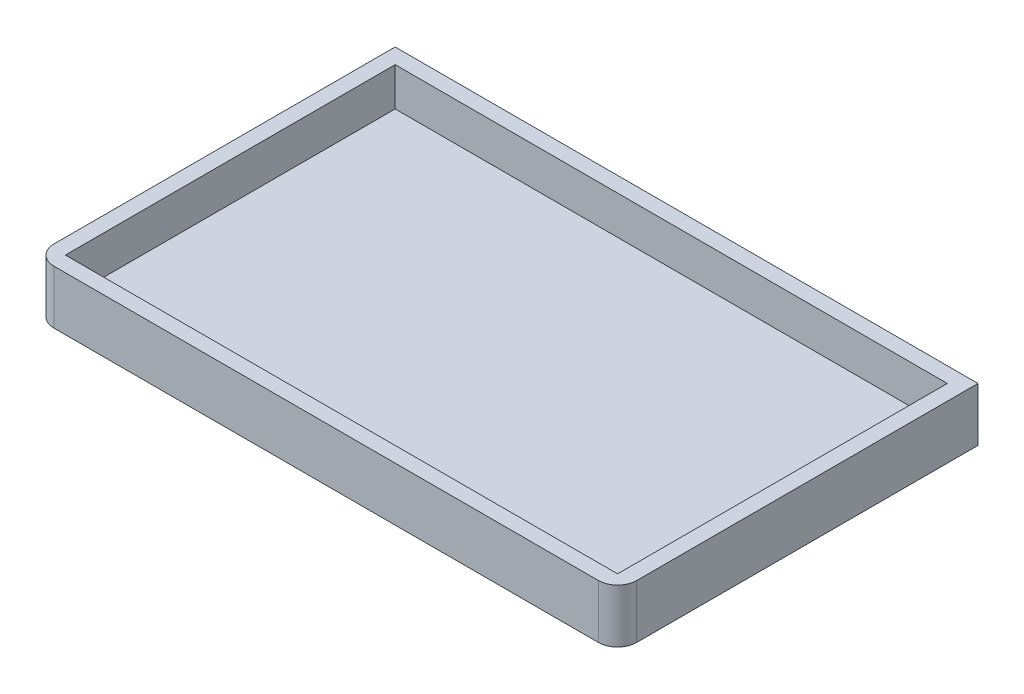
SolidWorks part; units mm, degrees
ref_plane "Front Plane" through (0, 0, 0) normal (0, 0, 1) x (1, 0, 0)
ref_plane "Top Plane" through (0, 0, 0) normal (0, 1, 0) x (1, 0, 0)
ref_plane "Right Plane" through (0, 0, 0) normal (1, 0, 0) x (0, 0, -1)
sketch "Sketch2" plane through (0, 0, 0) normal (0, 0, 1) x (1, 0, 0)
  line L1 (0, 0) -> (50, 0)
  line L2 (0, 0) -> (0, 41)
  line L3 (0, 41) -> (50, 41)
  line L4 (50, 0) -> (50, 41)
  dimension "D1" = 50
  dimension "D2" = 41
extrude "Boss-Extrude1" add sketch "Sketch2" along normal blind 4
sketch "Sketch4" plane through (0, 41, 0) normal (0, 1, 0) x (1, 0, 0)
  line L1 (-51, 0) -> (-51, -94)
  line L2 (101, 0) -> (101, -94)
  line L3 (-51, -94) -> (101, -94)
  line L4 (101, 0) -> (-51, 0) construction
  line L5 (25, 0) -> (25, -94) construction
  line L6 (-51, 0) -> (101, 0)
  line L7 (50, 0) -> (0, 0) construction
  point P1 (0, 0)
  point P4 (0, 0)
  dimension "D1" = 152
  dimension "D2" = 94
extrude "Boss-Extrude2" add sketch "Sketch4" along normal blind 14
sketch3d "3DSketch1"
  line L0 (97, 55, 90) -> (97, 55, 4)
  line L1 (97, 55, 4) -> (-47, 55, 4)
  line L2 (-47, 55, 4) -> (-47, 55, 90)
  line L3 (-47, 55, 90) -> (97, 55, 90)
  line L4 (97, 55, 90) -> (97, 55, 4)
  line L5 (97, 55, 4) -> (-47, 55, 4)
  line L6 (-47, 55, 4) -> (-47, 55, 90)
  line L7 (-47, 55, 90) -> (97, 55, 90)
  dimension "D1" = 4
extrude "Cut-Extrude1" cut sketch "3DSketch1" along direction (0, -1, 0) on the side of the normal blind 10
fillet "Fillet1" radius 5 2 edges at (101, 48, 94) (-51, 48, 94)
sketch "Sketch5" plane through (0, 0, 4) normal (0, 0, 1) x (1, 0, 0)
  line L0 (50, 41) -> (0, 41) construction
  line L1 (27, 41) -> (23, 41)
  line L2 (27, 41) -> (27, 0)
  line L3 (27, 0) -> (23, 0)
  line L4 (23, 41) -> (23, 0)
  line L5 (0, 0) -> (50, 0) construction
  line L6 (96, 41) -> (101, 41) construction
  line L7 (23, 20.5) -> (0, 20.5) construction
  line L8 (0, 41) -> (0, 0) construction
  line L9 (27, 20.5) -> (50, 20.5) construction
  line L10 (50, 0) -> (50, 41) construction
  dimension "D1" = 4
extrude "Boss-Extrude3" add sketch "Sketch5" along normal blind 80
sketch "Sketch6" plane through (27, 0, 0) normal (1, 0, 0) x (0, 0, -1)
  line L1 (-4, 0) -> (-84, 0)
  line L2 (-84, 0) -> (-84, 41)
  line L3 (-84, 41) -> (-68, 41)
  line L4 (-84, 41) -> (-4, 41) construction
  line L5 (-68, 41) -> (-4, 16)
  line L6 (-4, 0) -> (-4, 41) construction
  line L7 (-4, 16) -> (-4, 0)
  point P12 (-4, 17.929)
  dimension "D1" = 25
extrude "Cut-Extrude2" cut sketch "Sketch6" against normal up to surface (4 mm away) up to face at (23, 20.5, 44)
sketch "Sketch7" plane through (0, 0, 4) normal (0, 0, 1) x (1, 0, 0)
  line L0 (25, 16) -> (25, 0) construction
  line L1 (23, 16) -> (27, 16) construction
  line L2 (0, 0) -> (50, 0) construction
  line L3 (25, 8) -> (0, 8) construction
  line L4 (0, 41) -> (0, 0) construction
  line L5 (25, 8) -> (50, 8) construction
  line L6 (50, 0) -> (50, 41) construction
  line L7 (0, 20.5) -> (50, 20.5) construction
  circle A0 centre (12.5, 8) radius 2
  circle A1 centre (37.5, 8) radius 2
  circle A4 centre (37.5, 33) radius 2
  circle A5 centre (12.5, 33) radius 2
  dimension "D1" = 4
extrude "Cut-Extrude3" cut sketch "Sketch7" against normal up to surface (4 mm away) up to face at (25, 34.25, 0)
chamfer "Chamfer1" distance 1 angle 45 4 edges at (39.5, 8, 4) (14.5, 8, 4) (35.5, 33, 4) (10.5, 33, 4)
fillet "Fillet2" radius 5 2 edges at (0, 41, 2) (50, 41, 2)
